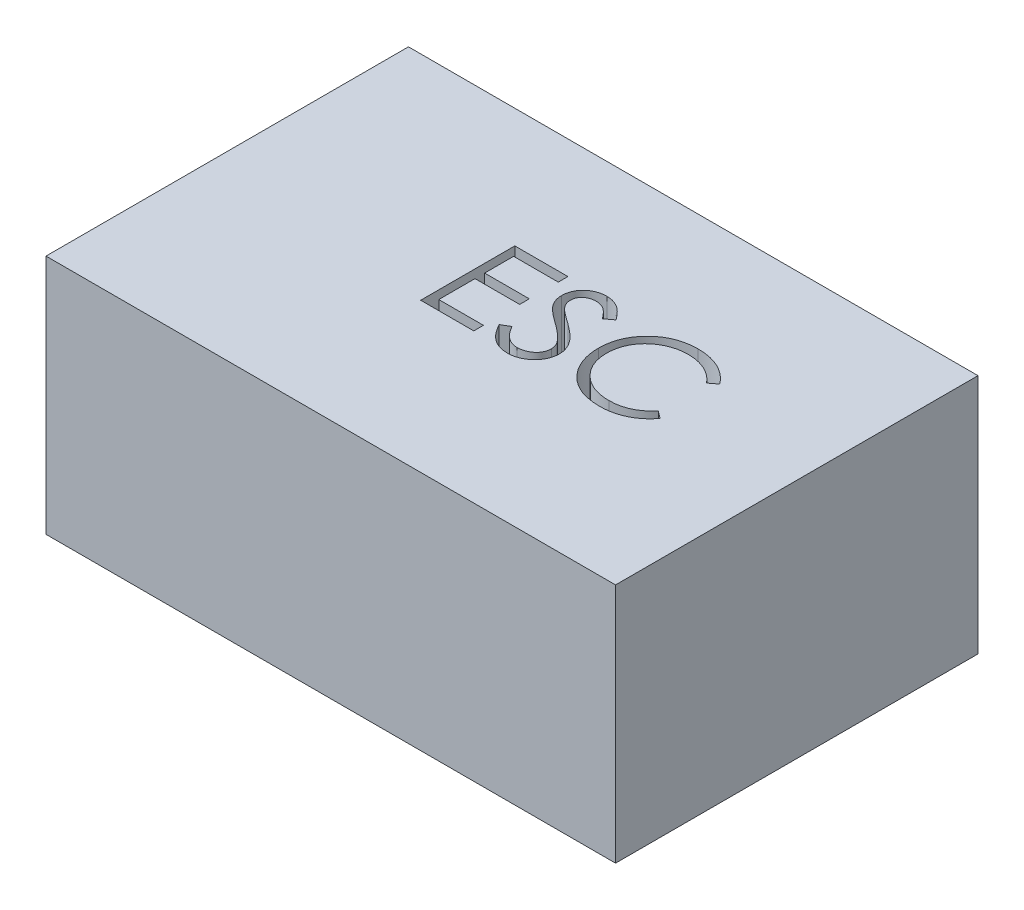
SolidWorks part; units mm, degrees
ref_plane "Front Plane" through (0, 0, 0) normal (0, 0, 1) x (1, 0, 0)
ref_plane "Top Plane" through (0, 0, 0) normal (0, 1, 0) x (1, 0, 0)
ref_plane "Right Plane" through (0, 0, 0) normal (1, 0, 0) x (0, 0, -1)
sketch "Sketch1" plane through (0, 0, 0) normal (0, 1, 0) x (1, 0, 0)
  line L1 (0, 0) -> (60.5, 0)
  line L2 (0, 0) -> (0, 38.5)
  line L3 (0, 38.5) -> (60.5, 38.5)
  line L4 (60.5, 0) -> (60.5, 38.5)
  dimension "D1" = 60.5
  dimension "D2" = 38.5
extrude "Boss-Extrude1" add sketch "Sketch1" along normal blind 25.6
sketch "Sketch2" plane through (0, 25.6, 0) normal (0, 1, 0) x (1, 0, 0)
  text T0 "ESC" font "Century Gothic" height 10
extrude "Cut-Extrude1" cut sketch "Sketch2" against normal blind 10
